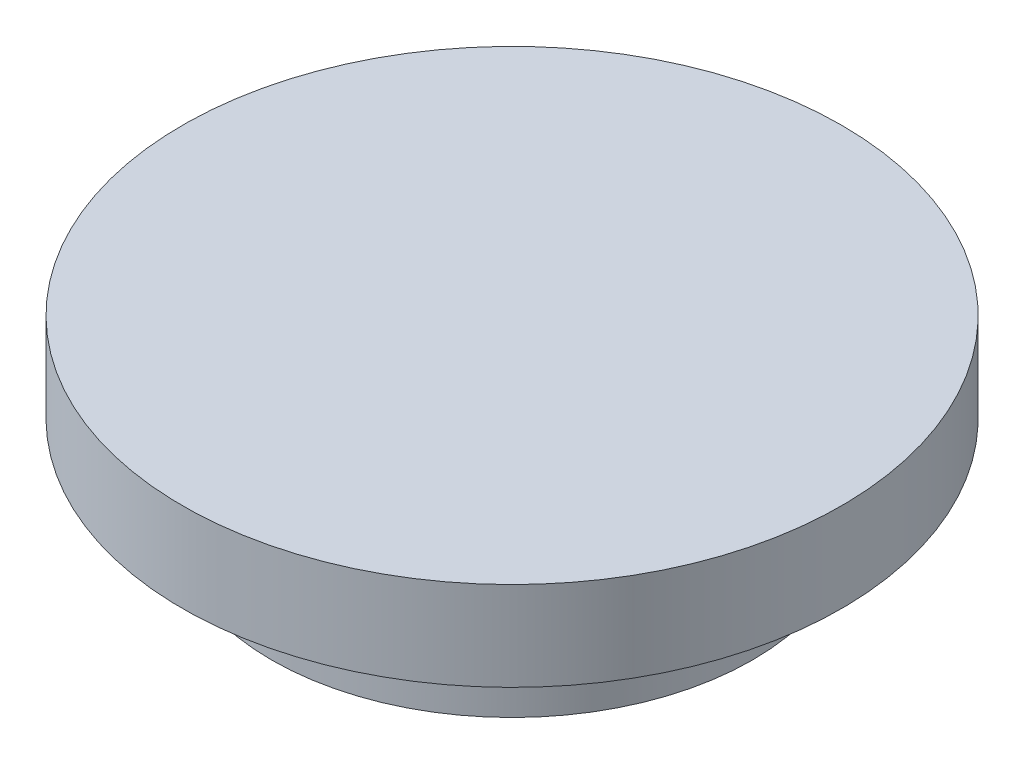
SolidWorks part; units mm, degrees
ref_plane "Ebene vorne" through (0, 0, 0) normal (0, 0, 1) x (1, 0, 0)
ref_plane "Ebene oben" through (0, 0, 0) normal (0, 1, 0) x (1, 0, 0)
ref_plane "Ebene rechts" through (0, 0, 0) normal (1, 0, 0) x (0, 0, -1)
sketch "Sketch1" plane through (0, 0, 0) normal (0, 0, 1) x (1, 0, 0)
  line L0 (0, 0) -> (0, 3.159) construction
  line L1 (1.35, 0) -> (1.35, 0.5)
  line L2 (1.35, 0.5) -> (1.85, 0.5)
  line L3 (1.85, 0.5) -> (1.85, 1)
  line L4 (1.85, 1) -> (0, 1)
  line L6 (0, 0) -> (1.35, 0)
  line L7 (0, 1) -> (0, 0)
  dimension "D1" = 2.7
  dimension "D2" = 0.5
  dimension "D3" = 0.5
  dimension "D4" = 0.5
revolve "Revolve1" add sketch "Sketch1" angle 360 about L0
